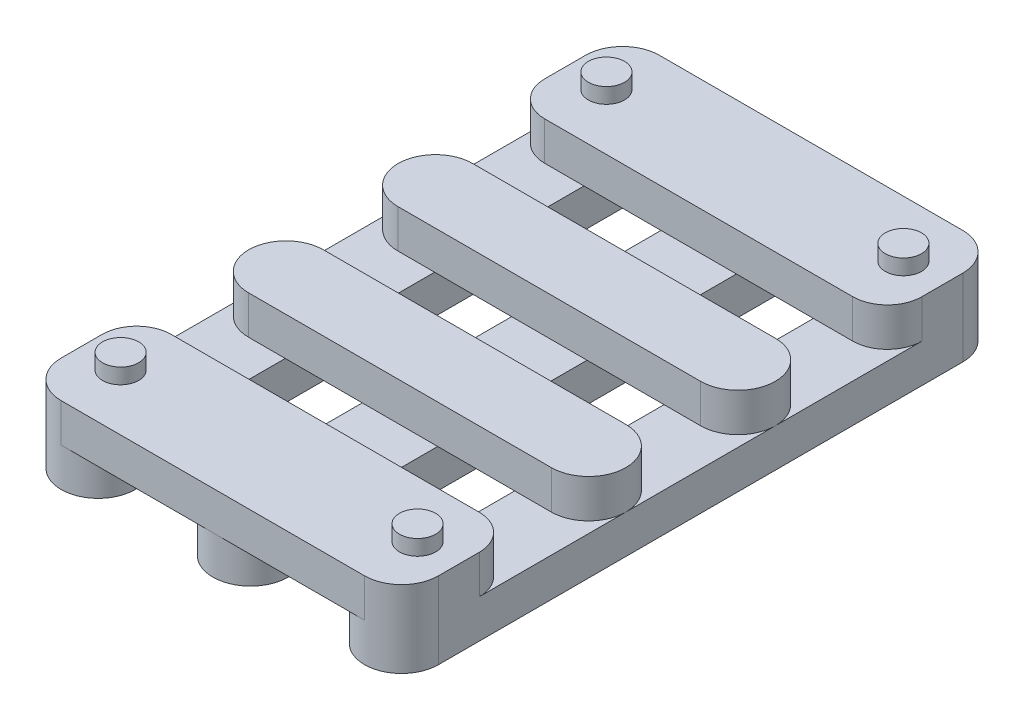
SolidWorks part; units mm, degrees
ref_plane "Front Plane" through (0, 0, 0) normal (0, 0, 1) x (1, 0, 0)
ref_plane "Top Plane" through (0, 0, 0) normal (0, 1, 0) x (1, 0, 0)
ref_plane "Right Plane" through (0, 0, 0) normal (1, 0, 0) x (0, 0, -1)
sketch "Sketch1" plane through (0, 0, 0) normal (0, 1, 0) x (1, 0, 0)
  line L1 (-23.3656, -38.85) -> (16.6344, -38.85)
  line L2 (-27.8656, -34.35) -> (-27.8656, 34.35)
  line L3 (-23.3656, 38.85) -> (16.6344, 38.85)
  line L4 (21.1344, -34.35) -> (21.1344, 34.35)
  arc A0 (-27.8656, -34.35) -> (-23.3656, -38.85) centre (-23.3656, -34.35) ccw
  arc A1 (21.1344, -34.35) -> (16.6344, -38.85) centre (16.6344, -34.35) cw
  arc A2 (-23.3656, 38.85) -> (-27.8656, 34.35) centre (-23.3656, 34.35) ccw
  arc A3 (21.1344, 34.35) -> (16.6344, 38.85) centre (16.6344, 34.35) ccw
  point P0 (0, 0)
  point P14 (21.1344, -38.85)
  point P17 (-27.8656, 38.85)
  point P20 (21.1344, 38.85)
  dimension "D5" = 4.5
  dimension "D1" = 77.7
  dimension "D2" = 49
extrude "Boss-Extrude1" add sketch "Sketch1" along normal blind 10 contours L2 A0 L1 A1 L4 A3 L3 A2
sketch "Sketch2" plane through (0, 10, 0) normal (0, 1, 0) x (1, 0, 0)
  line L0 (-23.3656, 24.25) -> (16.6344, 24.25)
  line L1 (-27.8656, 14.55) -> (21.1344, 14.55)
  line L2 (-27.8656, 4.85) -> (21.1344, 4.85)
  line L3 (-27.8656, -4.85) -> (21.1344, -4.85)
  line L4 (-27.8656, 34.35) -> (-27.8656, -34.35)
  line L5 (-23.3656, -38.85) -> (16.6344, -38.85)
  line L6 (21.1344, -34.35) -> (21.1344, 34.35)
  line L7 (16.6344, 38.85) -> (-23.3656, 38.85)
  line L8 (-27.8656, 34.35) -> (-27.8656, 28.75)
  line L9 (-23.3656, -38.85) -> (16.6344, -38.85)
  line L10 (21.1344, 28.75) -> (21.1344, 34.35)
  line L11 (16.6344, 38.85) -> (-23.3656, 38.85)
  line L12 (-27.8656, -14.55) -> (21.1344, -14.55)
  line L13 (21.1344, 14.55) -> (21.1344, 4.85)
  line L14 (-23.3656, -24.25) -> (16.6344, -24.25)
  line L15 (-27.8656, 14.55) -> (-27.8656, 4.85)
  line L16 (-27.8656, -4.85) -> (-27.8656, -14.55)
  line L17 (21.1344, -4.85) -> (21.1344, -14.55)
  line L18 (-27.8656, -28.75) -> (-27.8656, -33.2156)
  line L19 (-27.8656, -34.35) -> (-27.8656, 34.35) construction
  line L20 (21.1344, -28.75) -> (21.1344, -31.0612)
  line L21 (21.1344, -34.35) -> (21.1344, 34.35) construction
  arc A0 (21.1344, 28.75) -> (16.6344, 24.25) centre (16.6344, 28.75) cw
  arc A1 (-27.8656, 28.75) -> (-23.3656, 24.25) centre (-23.3656, 28.75) ccw
  circle A2 centre (16.2844, 9.7) radius 4.85
  circle A3 centre (16.2844, -9.7) radius 4.85
  arc A4 (-23.3656, 38.85) -> (-27.8656, 34.35) centre (-23.3656, 34.35) ccw
  arc A5 (-27.8656, -34.35) -> (-23.3656, -38.85) centre (-23.3656, -34.35) ccw
  arc A6 (16.6344, -38.85) -> (21.1344, -34.35) centre (16.6344, -34.35) ccw
  arc A7 (21.1344, 34.35) -> (16.6344, 38.85) centre (16.6344, 34.35) ccw
  arc A8 (-23.3656, 38.85) -> (-27.8656, 34.35) centre (-23.3656, 34.35) ccw
  arc A9 (-27.8656, -34.35) -> (-23.3656, -38.85) centre (-23.3656, -34.35) ccw
  arc A10 (16.6344, -38.85) -> (21.1344, -34.35) centre (16.6344, -34.35) ccw
  arc A11 (21.1344, 34.35) -> (16.6344, 38.85) centre (16.6344, 34.35) ccw
  circle A12 centre (-23.0156, 9.7) radius 4.85
  circle A13 centre (-23.0156, -9.7) radius 4.85
  arc A14 (16.6344, -24.25) -> (21.1344, -28.75) centre (16.6344, -28.75) cw
  arc A15 (-23.3656, -24.25) -> (-27.8656, -28.75) centre (-23.3656, -28.75) ccw
  point P28 (16.2844, 14.55)
  point P30 (17.6053, -4.85)
  point P31 (17.6053, -14.55)
  point P32 (-24.5992, -14.55)
  point P33 (-24.5992, -4.85)
  point P34 (-24.5992, 4.85)
  point P35 (-24.5992, 14.55)
  point P48 (21.1344, -24.25)
  point P54 (-27.8656, -24.25)
  line M16 (-27.8656, 34.35) -> (-27.8656, -34.35)
  line M20 (21.1344, -34.35) -> (21.1344, 34.35)
  dimension "D8" = 4.5
  dimension "D9" = 4.5
  dimension "D12" = 9.7
  dimension "D13" = 4.85
  dimension "D15" = 9.7
  dimension "D16" = 9.7
  dimension "D21" = 9.7
  dimension "D22" = 4.5
  dimension "D2" = 14.6
  dimension "D3" = 9.7
  dimension "D4" = 9.7
  dimension "D5" = 14.6
  dimension "D6" = 9.7
  dimension "D7" = 9.7
  dimension "D10" = 4.85
  dimension "D11" = 4.85
  dimension "D14" = 4.85
  dimension "D17" = 4.85
  dimension "D18" = 4.85
  dimension "D19" = 4.85
  dimension "D20" = 4.85
  dimension "D1" = 0
extrude "Cut-Extrude3" cut sketch "Sketch2" against normal blind 5 contours A15 L14 A14 L12 M20 M16 | A13 L16 L12 | A3 L12 M20 | A3 L17 L3 | A13 L3 M16 | L3 L2 M16 M20 | A12 L15 L2 | A2 L2 M20 | A12 L1 M16 | A1 L1 A0 L0 M16 M20 | A2 L13 L1
sketch "Sketch4" plane through (0, 0, 0) normal (0, -1, 0) x (1, 0, 0)
  line L0 (-18.1156, 38.85) -> (-18.1156, -38.85)
  line L1 (-8.2906, 38.85) -> (-8.2906, -38.85)
  line L2 (1.5594, 38.85) -> (1.5594, -38.85)
  line L3 (11.3844, 38.85) -> (11.3844, -38.85)
  line L4 (-23.3656, -38.85) -> (16.6344, -38.85)
  line L5 (21.1344, -34.35) -> (21.1344, 34.35)
  line L6 (16.6344, 38.85) -> (-23.3656, 38.85)
  line L7 (-27.8656, 34.35) -> (-27.8656, -34.35)
  line L8 (-23.3656, -38.85) -> (16.6344, -38.85)
  line L9 (21.1344, -34.35) -> (21.1344, 34.35)
  line L10 (16.6344, 38.85) -> (-23.3656, 38.85)
  line L11 (-27.8656, 34.35) -> (-27.8656, -34.35)
  line L12 (-27.8656, 34.1766) -> (-27.8656, 38.85)
  line L13 (-27.8656, 38.85) -> (-23.3656, 38.85)
  line L14 (-23.3656, 38.85) -> (-23.3656, 35.6156)
  line L15 (-23.3656, 35.6156) -> (-27.8656, 34.1766)
  line L16 (-27.8656, -34.35) -> (-27.8656, -38.85)
  line L17 (-27.8656, -38.85) -> (-23.3656, -38.85)
  line L18 (-23.1567, -35.5858) -> (-27.8656, -34.35)
  line L19 (-23.3656, -38.85) -> (-23.1567, -35.5858)
  line L20 (16.6344, -38.85) -> (21.1344, -38.85)
  line L21 (21.1344, -38.85) -> (21.1344, -34.35)
  line L22 (16.6344, -38.85) -> (16.6344, -34.745)
  line L23 (16.6344, -34.745) -> (21.1344, -34.35)
  line L24 (16.6344, 38.85) -> (21.1344, 38.85)
  line L25 (21.1344, 38.85) -> (21.1344, 34.35)
  line L26 (21.1344, 34.35) -> (17.4288, 36.8474)
  line L27 (17.4288, 36.8474) -> (16.6344, 38.85)
  arc A4 (-27.8656, -34.35) -> (-23.3656, -38.85) centre (-23.3656, -34.35) ccw
  arc A5 (16.6344, -38.85) -> (21.1344, -34.35) centre (16.6344, -34.35) ccw
  arc A6 (21.1344, 34.35) -> (16.6344, 38.85) centre (16.6344, 34.35) ccw
  arc A7 (-23.3656, 38.85) -> (-27.8656, 34.35) centre (-23.3656, 34.35) ccw
  arc A8 (-27.8656, -34.35) -> (-23.3656, -38.85) centre (-23.3656, -34.35) ccw
  arc A9 (16.6344, -38.85) -> (21.1344, -34.35) centre (16.6344, -34.35) ccw
  arc A10 (21.1344, 34.35) -> (16.6344, 38.85) centre (16.6344, 34.35) ccw
  arc A11 (-23.3656, 38.85) -> (-27.8656, 34.35) centre (-23.3656, 34.35) ccw
  arc M21 (-27.8656, -34.35) -> (-23.3656, -38.85) centre (-23.3656, -34.35) ccw
  arc M23 (16.6344, -38.85) -> (21.1344, -34.35) centre (16.6344, -34.35) ccw
  arc M25 (21.1344, 34.35) -> (16.6344, 38.85) centre (16.6344, 34.35) ccw
  arc M27 (-23.3656, 38.85) -> (-27.8656, 34.35) centre (-23.3656, 34.35) ccw
  line M28 (-27.8656, 34.35) -> (-27.8656, -34.35)
  dimension "D3" = 9.75
  dimension "D2" = 9.75
  dimension "D4" = 9.85
  dimension "D5" = 9.825
  dimension "D1" = 0
extrude "Boss-Extrude6" add sketch "Sketch4" along normal blind 5 and the other way blind 10 contours L13 L12 M27 | L15 L14 M27 M28 | L27 L26 M25 | L25 L24 M25 | L23 L22 M23 | L20 L21 M23 | L19 L18 M21 | L16 L17 M21
sketch "Sketch5" plane through (21.1344, 0, 0) normal (1, 0, 0) x (0, 0, -1)
  line L1 (-38.85, 0) -> (41.5848, 0)
  line L2 (-38.85, 0) -> (-38.85, -11.4679)
  line L3 (-38.85, -11.4679) -> (41.5848, -11.4679)
  line L4 (41.5848, 0) -> (41.5848, -11.4679)
  line L14 (9.7, 5) -> (-9.7, 5)
  line L15 (-9.7, 5) -> (-28.75, 5)
  line L16 (-28.75, 5) -> (-28.75, 10)
  line L17 (-28.75, 10) -> (-38.85, 10)
  line L18 (-38.85, 10) -> (-38.85, -5)
  line L19 (-38.85, -5) -> (-34.35, -5)
  line L20 (-34.35, -5) -> (-34.35, 0)
  line L21 (-34.35, 0) -> (34.35, 0)
  line L22 (34.35, 0) -> (34.35, -5)
  line L23 (34.35, -5) -> (38.85, -5)
  line L24 (38.85, -5) -> (38.85, 10)
  line L25 (38.85, 10) -> (28.75, 10)
  line L26 (28.75, 10) -> (28.75, 5)
  line L27 (28.75, 5) -> (9.7, 5)
  line L28 (9.7, 5) -> (-9.7, 5)
  line L29 (-9.7, 5) -> (-28.75, 5)
  line L30 (-28.75, 5) -> (-28.75, 10)
  line L31 (-28.75, 10) -> (-38.85, 10)
  line L32 (-38.85, 10) -> (-38.85, -5)
  line L33 (-38.85, -5) -> (-34.35, -5)
  line L34 (-34.35, -5) -> (-34.35, 0)
  line L35 (-34.35, 0) -> (34.35, 0)
  line L36 (34.35, 0) -> (34.35, -5)
  line L37 (34.35, -5) -> (38.85, -5)
  line L38 (38.85, -5) -> (38.85, 10)
  line L39 (38.85, 10) -> (28.75, 10)
  line L40 (28.75, 10) -> (28.75, 5)
  line L41 (28.75, 5) -> (9.7, 5)
  line M23 (-38.85, 10) -> (-38.85, -5)
  line M24 (-38.85, -5) -> (-34.35, -5)
  line M25 (-34.35, -5) -> (-34.35, 0)
  line M26 (-34.35, 0) -> (34.35, 0)
  line M27 (34.35, 0) -> (34.35, -5)
  line M28 (34.35, -5) -> (38.85, -5)
  line M29 (38.85, -5) -> (38.85, 10)
  dimension "D1" = 0
extrude "Cut-Extrude5" cut sketch "Sketch5" against normal blind 60 contours L4 L1 L2 L3 M29 M28 M27 M26 M25 M24 | L1 M27 M28 M29 | L1 M23 M24 M25
sketch "Sketch6" plane through (0, 0, 0) normal (0, -1, 0) x (1, 0, 0)
  line L0 (-18.2656, 38.85) -> (-18.2656, -38.85)
  line L1 (-8.2656, 38.85) -> (-8.2656, -38.85)
  line L2 (1.5344, 38.85) -> (1.5344, -38.85)
  line L3 (11.5344, 38.85) -> (11.5344, -38.85)
  line L4 (21.1344, 38.85) -> (-27.8656, 38.85)
  line L5 (-27.8656, 38.85) -> (-27.8656, -38.85)
  line L6 (-27.8656, -38.85) -> (21.1344, -38.85)
  line L7 (21.1344, -38.85) -> (21.1344, 38.85)
  line L8 (21.1344, 38.85) -> (-27.8656, 38.85)
  line L9 (-27.8656, 38.85) -> (-27.8656, -38.85)
  line L10 (-27.8656, -38.85) -> (21.1344, -38.85)
  line L11 (21.1344, -38.85) -> (21.1344, 38.85)
  circle A0 centre (-23.0656, 34.05) radius 4.8
  circle A1 centre (-23.0656, -34.05) radius 4.8
  circle A2 centre (16.3344, -34.05) radius 4.8
  circle A3 centre (16.3344, 34.05) radius 4.8
  circle A4 centre (-3.3656, 33.95) radius 4.9
  circle A5 centre (-3.3656, -33.95) radius 4.9
  line M15 (21.1344, 38.85) -> (-27.8656, 38.85)
  line M16 (-27.8656, 38.85) -> (-27.8656, -38.85)
  line M17 (-27.8656, -38.85) -> (21.1344, -38.85)
  line M18 (21.1344, -38.85) -> (21.1344, 38.85)
  dimension "D2" = 9.6
  dimension "D3" = 9.6
  dimension "D4" = 10
  dimension "D5" = 10
  dimension "D1" = 0
extrude "Cut-Extrude7" cut sketch "Sketch6" against normal blind 5 contours A0 L8 M16 | A0 L0 M15 | L1 L0 M15 M17 | A4 L8 L1 | A4 L2 M15 | L3 L2 M15 M17 | A3 L8 L3 | A3 M18 M15 | A2 L10 M18 | A2 L3 M17 | A5 L10 L2 | A5 L1 M17 | A1 L10 L0 | A1 M16 M17
sketch "Sketch8" plane through (0, 0, 0) normal (0, -1, 0) x (1, 0, 0)
  line L0 (-27.8656, 34.05) -> (-27.8656, 38.85)
  line L1 (-27.8656, 38.85) -> (-23.0656, 38.85)
  line L2 (-27.8656, -38.85) -> (-27.8656, -28.2476)
  line L3 (-27.8656, -38.85) -> (-20.4401, -38.85)
  line L4 (-23.0656, -38.85) -> (-3.3656, -38.85) construction
  line L5 (21.1344, -38.85) -> (21.1344, -31.0793)
  line L6 (21.1344, 34.05) -> (21.1344, -34.05) construction
  line L7 (21.1344, -38.85) -> (13.7173, -38.85)
  line L8 (-3.3656, -38.85) -> (16.3344, -38.85) construction
  line L9 (21.1344, 38.85) -> (12.7925, 38.85)
  line L10 (16.3344, 38.85) -> (-3.3656, 38.85) construction
  line L11 (21.1344, 38.85) -> (21.1344, 31.9948)
  circle A0 centre (-23.0656, 34.05) radius 4.8
  arc A3 (-18.2656, 34.05) -> (-27.8656, 34.05) centre (-23.0656, 34.05) ccw construction
  circle A4 centre (16.3344, 34.05) radius 4.8
  circle A5 centre (-23.0656, -34.05) radius 4.8
  circle A7 centre (16.3344, -34.05) radius 4.8
  arc A8 (21.1344, 34.05) -> (11.5344, 34.05) centre (16.3344, 34.05) ccw construction
  arc A9 (11.5344, -34.05) -> (21.1344, -34.05) centre (16.3344, -34.05) ccw construction
  arc A10 (-27.8656, -34.05) -> (-18.2656, -34.05) centre (-23.0656, -34.05) ccw construction
  arc M3 (-18.2656, 34.05) -> (-27.8656, 34.05) centre (-23.0656, 34.05) ccw
  arc M5 (-27.8656, -34.05) -> (-18.2656, -34.05) centre (-23.0656, -34.05) ccw
  dimension "D1" = 9.6
  dimension "D2" = 9.6
  dimension "D3" = 9.6
  dimension "D4" = 9.6
extrude "Cut-Extrude9" cut sketch "Sketch8" against normal blind 14 contours L1 L0 M3 | A4 L11 L9 | A7 L7 L5 | L2 L3 M5
sketch "Sketch9" plane through (0, 10, 0) normal (0, 1, 0) x (1, 0, 0)
  line L0 (16.3344, 38.85) -> (-23.0656, 38.85) construction
  line L1 (-27.8656, 34.05) -> (-27.8656, 28.75) construction
  line L2 (-23.3656, 24.25) -> (16.6344, 24.25) construction
  line L3 (21.1344, 28.75) -> (21.1344, 34.05) construction
  line L4 (-23.0656, -38.85) -> (16.3344, -38.85) construction
  line L5 (21.1344, -34.05) -> (21.1344, -28.75) construction
  line L6 (16.6344, -24.25) -> (-23.3656, -24.25) construction
  line L7 (-27.8656, -28.75) -> (-27.8656, -34.05) construction
  line L8 (16.3344, 38.85) -> (-23.0656, 38.85)
  line L9 (-27.8656, 34.05) -> (-27.8656, 28.75)
  line L10 (-23.3656, 24.25) -> (16.6344, 24.25)
  line L11 (21.1344, 28.75) -> (21.1344, 34.05)
  line L12 (-23.0656, -38.85) -> (16.3344, -38.85)
  line L13 (21.1344, -34.05) -> (21.1344, -28.75)
  line L14 (16.6344, -24.25) -> (-23.3656, -24.25)
  line L15 (-27.8656, -28.75) -> (-27.8656, -34.05)
  arc A0 (-23.0656, 38.85) -> (-27.8656, 34.05) centre (-23.0656, 34.05) ccw construction
  arc A1 (-27.8656, 28.75) -> (-23.3656, 24.25) centre (-23.3656, 28.75) ccw construction
  arc A2 (16.6344, 24.25) -> (21.1344, 28.75) centre (16.6344, 28.75) ccw construction
  arc A3 (21.1344, 34.05) -> (16.3344, 38.85) centre (16.3344, 34.05) ccw construction
  arc A4 (16.3344, -38.85) -> (21.1344, -34.05) centre (16.3344, -34.05) ccw construction
  arc A5 (21.1344, -28.75) -> (16.6344, -24.25) centre (16.6344, -28.75) ccw construction
  arc A6 (-23.3656, -24.25) -> (-27.8656, -28.75) centre (-23.3656, -28.75) ccw construction
  arc A7 (-27.8656, -34.05) -> (-23.0656, -38.85) centre (-23.0656, -34.05) ccw construction
  arc A8 (-23.0656, 38.85) -> (-27.8656, 34.05) centre (-23.0656, 34.05) ccw
  arc A9 (-27.8656, 28.75) -> (-23.3656, 24.25) centre (-23.3656, 28.75) ccw
  arc A10 (16.6344, 24.25) -> (21.1344, 28.75) centre (16.6344, 28.75) ccw
  arc A11 (21.1344, 34.05) -> (16.3344, 38.85) centre (16.3344, 34.05) ccw
  arc A12 (16.3344, -38.85) -> (21.1344, -34.05) centre (16.3344, -34.05) ccw
  arc A13 (21.1344, -28.75) -> (16.6344, -24.25) centre (16.6344, -28.75) ccw
  arc A14 (-23.3656, -24.25) -> (-27.8656, -28.75) centre (-23.3656, -28.75) ccw
  arc A15 (-27.8656, -34.05) -> (-23.0656, -38.85) centre (-23.0656, -34.05) ccw
  circle A16 centre (-22.6506, 31.55) radius 2.35
  circle A17 centre (15.9194, 31.55) radius 2.35
  circle A18 centre (-22.6506, -31.55) radius 2.35
  circle A19 centre (15.9194, -31.55) radius 2.35
  dimension "D1" = 4.7
  dimension "D2" = 4.7
  dimension "D3" = 4.7
  dimension "D4" = 4.7
  dimension "D5" = 38.57
  dimension "D6" = 7.3
  dimension "D7" = 7.3
  dimension "D8" = 5.215
  dimension "D9" = 38.57
  dimension "D10" = 7.3
  dimension "D11" = 5.215
  dimension "D12" = 7.3
extrude "Boss-Extrude7" add sketch "Sketch9" along normal blind 2 contours A17 | A16 | A19 | A18
sketch "Sketch12" plane through (0, 0, 0) normal (0, -1, 0) x (1, 0, 0)
  line L0 (-18.2656, -34.05) -> (-18.2656, 34.05) construction
  line L1 (-27.8656, 34.05) -> (-27.8656, -34.05) construction
  line L2 (11.5344, 34.05) -> (11.5344, -34.05) construction
  line L3 (21.1344, -34.05) -> (21.1344, 34.05) construction
  line L4 (-18.2656, -34.05) -> (-18.2656, 34.05)
  line L5 (-27.8656, 34.05) -> (-27.8656, -34.05)
  line L6 (11.5344, 34.05) -> (11.5344, -34.05)
  line L7 (21.1344, -34.05) -> (21.1344, 34.05)
  arc A0 (-18.2656, 34.05) -> (-27.8656, 34.05) centre (-23.0656, 34.05) ccw construction
  arc A1 (-27.8656, -34.05) -> (-18.2656, -34.05) centre (-23.0656, -34.05) ccw construction
  arc A2 (21.1344, 34.05) -> (11.5344, 34.05) centre (16.3344, 34.05) ccw construction
  arc A3 (11.5344, -34.05) -> (21.1344, -34.05) centre (16.3344, -34.05) ccw construction
  arc A4 (-18.2656, 34.05) -> (-27.8656, 34.05) centre (-23.0656, 34.05) ccw
  arc A5 (-27.8656, -34.05) -> (-18.2656, -34.05) centre (-23.0656, -34.05) ccw
  arc A6 (21.1344, 34.05) -> (11.5344, 34.05) centre (16.3344, 34.05) ccw
  arc A7 (11.5344, -34.05) -> (21.1344, -34.05) centre (16.3344, -34.05) ccw
  circle A8 centre (15.9194, 31.55) radius 2.35
  circle A10 centre (-22.6506, -31.55) radius 2.35
  circle A11 centre (-22.6506, 31.55) radius 2.35
  circle A12 centre (15.9194, -31.5847) radius 2.35
  dimension "D2" = 4.7
  dimension "D5" = 4.7
  dimension "D9" = 4.7
  dimension "D11" = 4.7
  dimension "D1" = 2.5
  dimension "D3" = 5.215
  dimension "D4" = 2.5
  dimension "D6" = 5.215
  dimension "D7" = 2.5
  dimension "D8" = 5.215
  dimension "D10" = 2.5
  dimension "D12" = 5.215
extrude "Cut-Extrude10" cut sketch "Sketch12" against normal blind 2 contours A8 | A11 | A12 | A10
